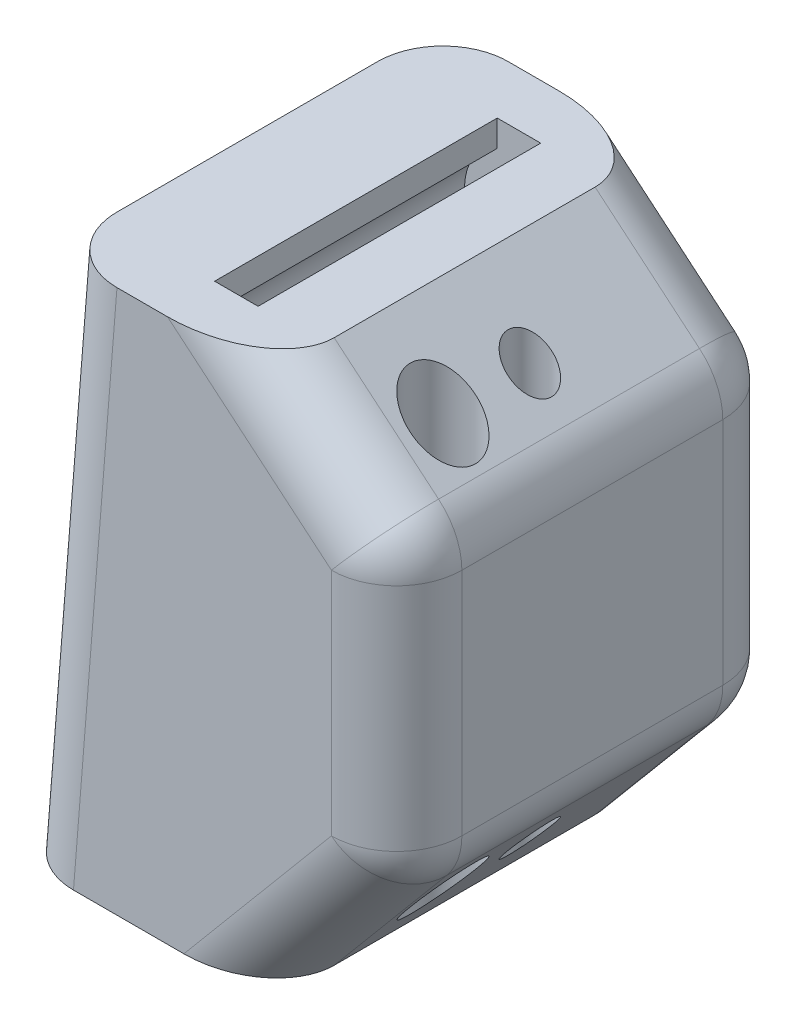
SolidWorks part; units mm, degrees
ref_plane "Front Plane" through (0, 0, 0) normal (0, 0, 1) x (1, 0, 0)
ref_plane "Top Plane" through (0, 0, 0) normal (0, 1, 0) x (1, 0, 0)
ref_plane "Right Plane" through (0, 0, 0) normal (1, 0, 0) x (0, 0, -1)
sketch "Sketch2" plane through (0, 0, 0) normal (0, 0, 1) x (1, 0, 0)
  line L0 (0, 0) -> (12, 0)
  line L1 (12, 0) -> (17.1718, 6.1635)
  line L2 (0, 0) -> (2, 25)
  line L3 (2, 25) -> (12, 25)
  line L4 (12, 25) -> (16.8021, 20.9706)
  line L5 (17.8737, 18.6725) -> (17.8737, 8.0919)
  arc A0 (16.8021, 20.9706) -> (17.8737, 18.6725) centre (14.8737, 18.6725) cw
  arc A1 (17.1718, 6.1635) -> (17.8737, 8.0919) centre (14.8737, 8.0919) ccw
  point P9 (17.8737, 20.0714)
  point P12 (17.8737, 7)
  dimension "D8" = 3
  dimension "D9" = 3
  dimension "D1" = 12
  dimension "D2" = 130
  dimension "D3" = 7
  dimension "D4" = 2
  dimension "D5" = 25
  dimension "D6" = 10
  dimension "D7" = 140
extrude "Boss-Extrude1" add sketch "Sketch2" along normal blind 18
sketch "Sketch3" plane through (0, 0, 18) normal (0, 0, 1) x (1, 0, 0)
  line L0 (12, 25) -> (2, 25) construction
  line L2 (7, 25) -> (9, 25)
  line L3 (7, 25) -> (7, 23.7913)
  line L5 (9, 25) -> (9, 23.7913)
  arc A0 (7, 23.7913) -> (9, 23.7913) centre (8, 21.5) ccw
  point P0 (8, 25)
  dimension "D2" = 5
  dimension "D1" = 8
  dimension "D3" = 3.5
  dimension "D4" = 2
  dimension "D5" = 1
extrude "Cut-Extrude1" cut sketch "Sketch3" against normal blind 13 from offset 2.5 offset against normal yes
sketch "Sketch4" plane through (0, 0, 0) normal (0, 0, -1) x (-1, 0, 0)
  line L0 (0, 0) -> (-12, 0) construction
  line L2 (-9, 0) -> (-7, 0)
  line L3 (-9, 0) -> (-9, 1.2087)
  line L5 (-7, 0) -> (-7, 1.2087)
  arc A0 (-7, 1.2087) -> (-9, 1.2087) centre (-8, 3.5) ccw
  point P0 (-8, 0)
  dimension "D2" = 5
  dimension "D1" = 8
  dimension "D3" = 3.5
  dimension "D4" = 2
  dimension "D5" = 1
extrude "Cut-Extrude2" cut sketch "Sketch4" against normal blind 13 from offset 2.5 offset against normal yes
sketch "Sketch5" plane through (0, 0, 0) normal (0, 1, 0) x (1, 0, 0)
  line L0 (12, -18) -> (12, 0) construction
  circle A0 centre (15, -9) radius 1
  circle A1 centre (15, -13) radius 1.5
  point P0 (12, -9)
  point P8 (0, 0)
  dimension "D1" = 2
  dimension "D4" = 3
  dimension "D2" = 3
  dimension "D3" = 15
  dimension "D5" = 4
extrude "Cut-Extrude3" cut sketch "Sketch5" along normal blind 25
fillet "Fillet1" radius 3 12 edges at (14.5859, 3.0818, 0) (17.6928, 7.0659, 0) (14.401, 22.9853, 0) (17.5926, 19.9403, 0) (14.5859, 3.0818, 18) (17.6928, 7.0659, 18) (14.401, 22.9853, 18) (17.5926, 19.9403, 18) (1, 12.5, 0) (17.8737, 13.3822, 0) (1, 12.5, 18) (17.8737, 13.3822, 18)
ref_plane "Plane1" through (0, 0, 9) normal (0, 0, 1) x (1, 0, 0)
